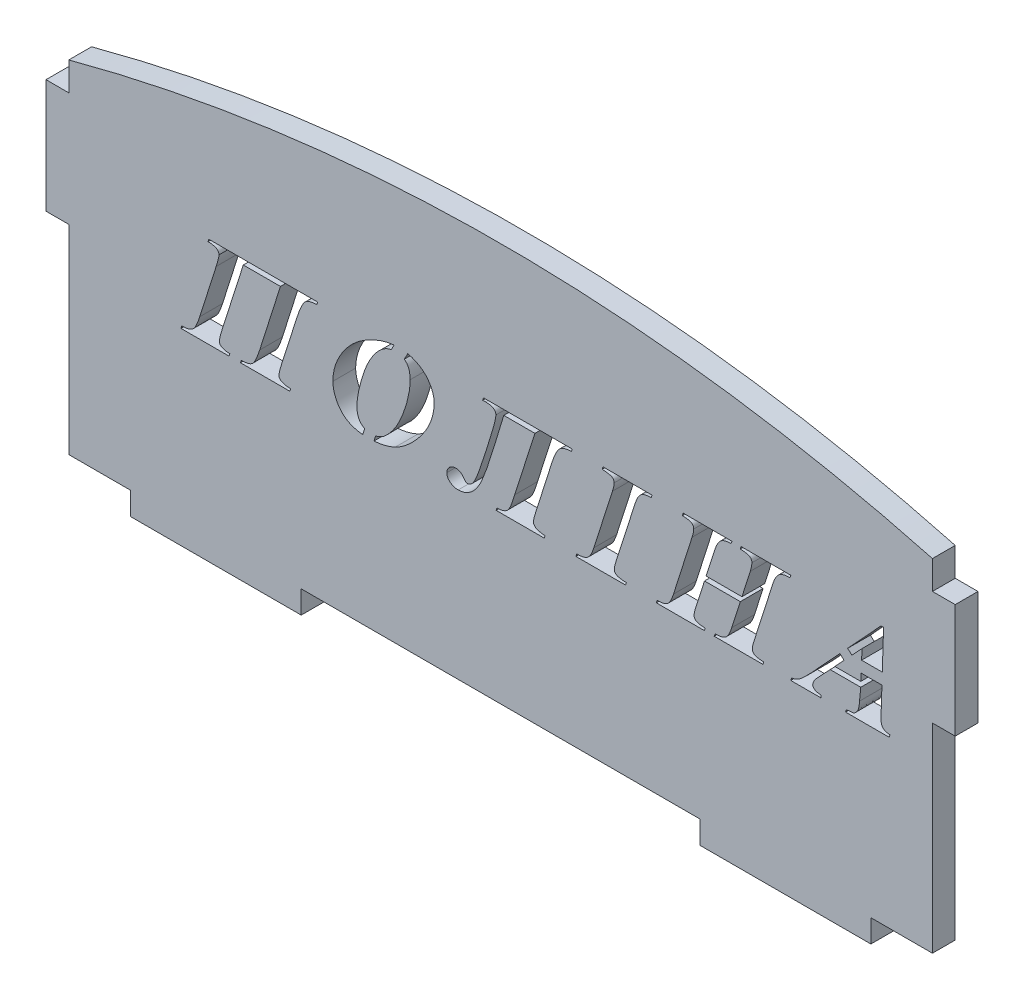
SolidWorks part; units mm, degrees
ref_plane "Спереди" through (0, 0, 0) normal (0, 0, 1) x (1, 0, 0)
ref_plane "Сверху" through (0, 0, 0) normal (0, 1, 0) x (1, 0, 0)
ref_plane "Справа" through (0, 0, 0) normal (1, 0, 0) x (0, 0, -1)
sketch "Эскиз1" plane through (0, 0, 0) normal (0, 0, 1) x (1, 0, 0)
  line L0 (125.8, -4) -> (125.8, 0) construction
  line L1 (0, 0) -> (151.6, 0)
  line L2 (0, 0) -> (0, 60)
  line L3 (0, 60) -> (151.6, 60) construction
  line L4 (151.6, 0) -> (151.6, 60)
  line L5 (10.8, 0) -> (40.8, 0)
  line L6 (10.8, 0) -> (10.8, -4)
  line L7 (10.8, -4) -> (40.8, -4)
  line L8 (40.8, 0) -> (40.8, -4)
  line L9 (110.8, 0) -> (140.8, 0)
  line L10 (110.8, 0) -> (110.8, -4)
  line L11 (110.8, -4) -> (140.8, -4)
  line L12 (140.8, 0) -> (140.8, -4)
  line L13 (25.8, -4) -> (25.8, 0) construction
  line L14 (75.8, 0) -> (75.8, -13.9957) construction
  line L15 (0, 35) -> (151.6, 35) construction
  line L16 (0, 55) -> (-4, 55)
  line L17 (0, 55) -> (0, 35)
  line L18 (0, 35) -> (-4, 35)
  line L19 (-4, 55) -> (-4, 35)
  line L20 (151.6, 55) -> (155.6, 55)
  line L21 (151.6, 55) -> (151.6, 35)
  line L22 (151.6, 35) -> (155.6, 35)
  line L23 (155.6, 55) -> (155.6, 35)
  arc A0 (0, 60) -> (151.6, 60) centre (75.8, -222.282) cw
  dimension "D3" = 20
  dimension "D1" = 151.6
  dimension "D2" = 60
  dimension "D4" = 30
  dimension "D5" = 30
  dimension "D6" = 4
  dimension "D7" = 4
  dimension "D8" = 50
  dimension "D9" = 50
  dimension "D10" = 4
  dimension "D11" = 4
  dimension "D12" = 20
  dimension "D13" = 20
  dimension "D14" = 35
extrude "Бобышка-Вытянуть1" add sketch "Эскиз1" along normal blind 4 contours A0 L2 L1 L4 | L8 L1 L6 L7 | L12 L1 L10 L11 | L16 L19 L18 L2 | L23 L20 L4 L22
sketch "Эскиз2" plane through (0, 0, 4) normal (0, 0, 1) x (1, 0, 0)
  line L0 (20.8, 29.0336) -> (130.8, 29.0336) construction
  line L1 (75.8, 0) -> (75.8, 29.0336) construction
  line L2 (40.8, 0) -> (110.8, 0) construction
  text T0 "<i>ПОЛІНА</i>" font "Times New Roman" height 16
  dimension "D1" = 110
extrude "Вырез-Вытянуть1" cut sketch "Эскиз2" against normal through all
sketch "Эскиз3" plane through (0, 0, 4) normal (0, 0, 1) x (1, 0, 0)
  line L0 (57.4201, 45.8017) -> (56.2088, 43.5133)
  line L1 (59.7299, 45.5315) -> (58.0249, 42.3103)
  line L2 (52.5268, 31.7747) -> (51.5329, 28.6353)
  line L3 (54.6792, 32.3342) -> (53.4164, 28.3455)
  line L19 (139.1659, 38.3335) -> (142.8001, 38.3335)
  line L20 (139.0222, 35.0336) -> (139.2444, 40.1377) construction
  line L21 (143.0222, 45.2558) -> (142.6056, 32.2731) construction
  line L22 (142.8001, 38.3335) -> (142.7359, 36.3335)
  line L23 (142.7359, 36.3335) -> (139.0788, 36.3335)
  line L24 (139.0788, 36.3335) -> (139.1659, 38.3335)
  line L25 (136.72, 38.9156) -> (137.4609, 38.231)
  line L26 (130.1819, 31.8391) -> (142.5778, 45.2558) construction
  line L27 (139.2444, 40.1377) -> (134.4701, 35.0336) construction
  line L28 (137.4609, 38.231) -> (136.0947, 36.7703)
  line L29 (136.0947, 36.7703) -> (135.3627, 37.4466)
  line L30 (135.3627, 37.4466) -> (136.72, 38.9156)
  arc A0 (56.2088, 43.5133) -> (58.0249, 42.3103) centre (56.8605, 42.5248) cw
  arc A1 (57.4201, 45.8017) -> (59.7299, 45.5315) centre (56.0759, 24.3027) cw
  arc A2 (52.5268, 31.7747) -> (54.6792, 32.3342) centre (52.3274, 36.9614) ccw
  arc A3 (53.4164, 28.3455) -> (51.5329, 28.6353) centre (45.0593, -19.6959) ccw
  point P16 (137.1586, 37.9078)
  point P23 (137.1586, 37.9078)
  point P24 (0, 0)
  point P27 (135.7287, 37.1085)
  point P28 (137.0447, 37.786)
  point P29 (134.8061, 36.8441)
  point P30 (136.0947, 36.7703)
  point P31 (59.9463, 46.0179)
  point P32 (58.0249, 42.3103)
  point P33 (56.9808, 45.1994)
  point P34 (57.4201, 45.8017)
  point P39 (59.5739, 45.0818)
  point P40 (59.7299, 45.5315)
  point P42 (57.2837, 45.227)
  point P43 (0, 0)
  dimension "D1" = 2
  dimension "D2" = 2
extrude "Бобышка-Вытянуть2" add sketch "Эскиз3" against normal blind 4 contours A1 L0 A0 L1 | A3 L3 A2 L2 | L24 L23 L22 L19 | L30 L29 L28 L25
sketch "Эскиз4" plane through (0, 0, 4) normal (0, 0, 1) x (1, 0, 0)
  circle A0 centre (76.2893, 33.6286) radius 6
  line B0 (76.2893, 65.5261) -> (76.2893, 43.3117) construction
  line B1 (76.2893, 33.6286) -> (76.2893, 43.3117) construction
  spline B2 degree 3 poles (78.3279, 43.291) (73.0677, 43.0403) (71.9181, 49.6251) (71.6314, 54.8846) (70.23, 60.1794) (73.4252, 66.4248) (82.8729, 65.2152) (84.4105, 56.9433) (81.9261, 51.238) (80.6373, 46.8237) (78.3279, 43.291) (73.0677, 43.0403) (71.9181, 49.6251) knots -0.21505 -0.114805 -0.058658 0 0.119421 0.222513 0.306807 0.406804 0.546838 0.690237 0.78495 0.885195 0.941342 1 1.119421 1.222513 1.306807 only from (74.7872, 43.5785) to (74.7872, 43.5785)
  spline B3 degree 3 poles (85.1148, 38.0592) (81.639, 42.0154) (86.0705, 47.0198) (90.0038, 50.5232) (93.2697, 54.9201) (100.1447, 56.316) (105.0896, 48.1752) (99.581, 41.8157) (93.5714, 40.2009) (89.3166, 38.4562) (85.1148, 38.0592) (81.639, 42.0154) (86.0705, 47.0198) knots -0.21505 -0.114805 -0.058658 0 0.119421 0.222513 0.306807 0.406804 0.546838 0.690237 0.78495 0.885195 0.941342 1 1.119421 1.222513 1.306807 only from (83.132, 41.0067) to (83.132, 41.0067)
  spline B4 degree 3 poles (85.2559, 29.4911) (86.1819, 34.6751) (92.8575, 34.3306) (98.0489, 33.4398) (103.5228, 33.6279) (108.9006, 29.1231) (105.619, 20.1814) (97.2124, 20.523) (92.203, 24.2147) (88.1861, 26.4535) (85.2559, 29.4911) (86.1819, 34.6751) (92.8575, 34.3306) knots -0.21505 -0.114805 -0.058658 0 0.119421 0.222513 0.306807 0.406804 0.546838 0.690237 0.78495 0.885195 0.941342 1 1.119421 1.222513 1.306807 only from (86.324, 32.879) to (86.324, 32.879)
  spline B5 degree 3 poles (78.6451, 24.0385) (83.2755, 26.5468) (87.1683, 21.1128) (89.7086, 16.4986) (93.2686, 12.3362) (93.0996, 5.323) (84.0627, 2.3135) (79.0883, 9.0991) (78.8513, 15.3173) (78.0971, 19.8537) (78.6451, 24.0385) (83.2755, 26.5468) (87.1683, 21.1128) knots -0.21505 -0.114805 -0.058658 0 0.119421 0.222513 0.306807 0.406804 0.546838 0.690237 0.78495 0.885195 0.941342 1 1.119421 1.222513 1.306807 only from (81.9598, 25.3158) to (81.9598, 25.3158)
  spline B6 degree 3 poles (70.2603, 25.8075) (75.1084, 23.7512) (73.287, 17.3196) (71.2633, 12.4566) (70.2287, 7.0781) (64.6401, 2.8375) (56.6528, 8.0265) (58.8565, 16.1464) (63.5704, 20.2087) (66.6468, 23.6267) (70.2603, 25.8075) (75.1084, 23.7512) (73.287, 17.3196) knots -0.21505 -0.114805 -0.058658 0 0.119421 0.222513 0.306807 0.406804 0.546838 0.690237 0.78495 0.885195 0.941342 1 1.119421 1.222513 1.306807 only from (73.3256, 24.0123) to (73.3256, 24.0123)
  spline B7 degree 3 poles (66.4156, 33.4659) (67.8305, 28.3934) (61.6665, 25.8074) (56.6027, 24.3576) (51.7526, 21.8131) (44.9528, 23.5384) (44.0297, 33.0184) (51.752, 36.3581) (57.8671, 35.2055) (62.4576, 34.9313) (66.4156, 33.4659) (67.8305, 28.3934) (61.6665, 25.8074) knots -0.21505 -0.114805 -0.058658 0 0.119421 0.222513 0.306807 0.406804 0.546838 0.690237 0.78495 0.885195 0.941342 1 1.119421 1.222513 1.306807 only from (66.9232, 29.9501) to (66.9232, 29.9501)
  spline B8 degree 3 poles (70.006, 41.2468) (66.9224, 36.9779) (61.0573, 40.1847) (56.7666, 43.2398) (51.7532, 45.4454) (48.8625, 51.8374) (55.6988, 58.4698) (63.1246, 54.5145) (66.0362, 49.0149) (68.6839, 45.2549) (70.006, 41.2468) (66.9224, 36.9779) (61.0573, 40.1847) knots -0.21505 -0.114805 -0.058658 0 0.119421 0.222513 0.306807 0.406804 0.546838 0.690237 0.78495 0.885195 0.941342 1 1.119421 1.222513 1.306807 only from (67.5736, 38.6579) to (67.5736, 38.6579)
  dimension "D1" = 12
sketch_block_instance "Блок1-1"
sketch_block "Блок1"
extrude "Вырез-Вытянуть2" [suppressed] cut sketch "Эскиз4" against normal blind 10
